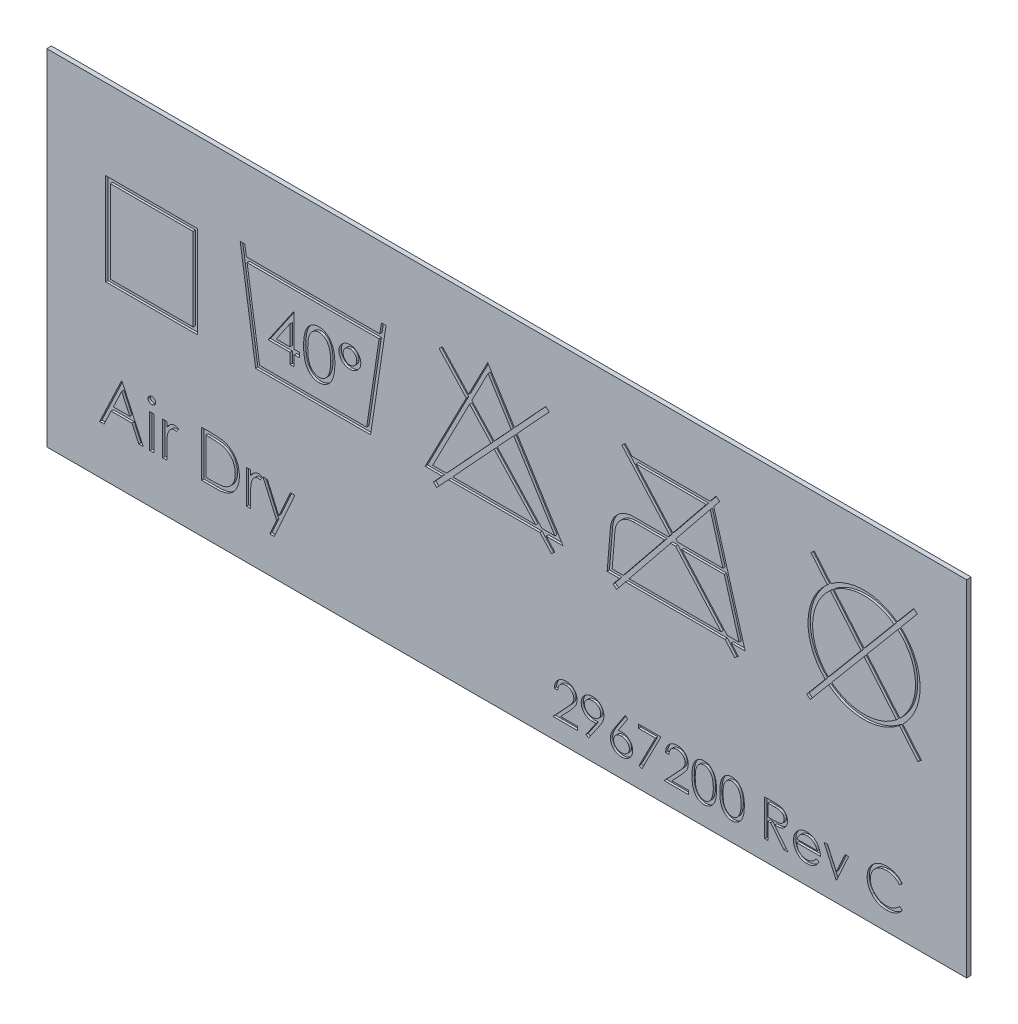
SolidWorks part; units mm, degrees
ref_plane "Plan de face" through (0, 0, 0) normal (0, 0, 1) x (1, 0, 0)
ref_plane "Plan de dessus" through (0, 0, 0) normal (0, 1, 0) x (1, 0, 0)
ref_plane "Plan de droite" through (0, 0, 0) normal (1, 0, 0) x (0, 0, -1)
sketch "Esquisse1" plane through (0, 0, 0) normal (0, 0, 1) x (1, 0, 0)
  line L1 (0, 0) -> (40, 0)
  line L3 (0, 15) -> (40, 15)
  line L4 (40, 0) -> (40, 15)
  line L5 (0, 15) -> (0, 0)
  point P7 (0, 0)
  dimension "D1" = 40
  dimension "D2" = 15
extrude "Extrusion1" add sketch "Esquisse1" along normal blind 0.2
sketch "Esquisse2" plane through (0, 0, 0.2) normal (0, 0, 1) x (1, 0, 0)
  line L0 (0, 7.5) -> (40, 7.5) construction
  line L2 (40, 0) -> (40, 15) construction
  line L3 (2.7616, 11.3) -> (6.3616, 11.3)
  line L4 (2.5616, 7.5) -> (6.5616, 7.5)
  line L5 (2.5616, 7.5) -> (2.5616, 11.5)
  line L6 (2.5616, 11.5) -> (6.5616, 11.5)
  line L7 (6.5616, 7.5) -> (6.5616, 11.5)
  line L8 (6.3616, 7.7) -> (6.3616, 11.3)
  line L9 (2.7616, 7.7) -> (6.3616, 7.7)
  line L10 (2.7616, 7.7) -> (2.7616, 11.3)
  line L11 (0, 15) -> (0, 0) construction
  dimension "D1" = 4
  dimension "D2" = 4
  dimension "D4" = 2.5616
  dimension "D3" = 0.2
extrude "Extrusion2" cut sketch "Esquisse2" against normal blind 0.1
sketch "Esquisse4" plane through (0, 0, 0.2) normal (0, 0, 1) x (1, 0, 0)
  line L0 (9.0813, 7.5) -> (14.0813, 7.5)
  line L1 (9.0813, 7.5) -> (8.4097, 11.9496)
  line L2 (13.9092, 7.7) -> (14.4525, 11.3)
  line L3 (14.0813, 7.5) -> (14.7528, 11.9496)
  line L4 (9.2534, 7.7) -> (13.9092, 7.7)
  line L5 (9.2534, 7.7) -> (8.71, 11.3)
  line L6 (8.4097, 11.9496) -> (8.612, 11.9496)
  line L7 (14.7528, 11.9496) -> (14.5506, 11.9496)
  line L8 (8.6799, 11.5) -> (14.4827, 11.5)
  line L9 (13.9092, 7.7) -> (14.5551, 11.9795) construction
  line L10 (9.2534, 7.7) -> (8.6075, 11.9795) construction
  line L11 (8.71, 11.3) -> (14.4525, 11.3)
  line L12 (8.6799, 11.5) -> (8.612, 11.9496)
  line L13 (8.6799, 11.3) -> (14.4827, 11.3) construction
  line L14 (14.4827, 11.5) -> (14.5506, 11.9496)
  dimension "D1" = 0.2
  dimension "D2" = 0.2
extrude "Extrusion3" cut sketch "Esquisse4" against normal blind 0.1
sketch "Esquisse5" plane through (0, 0, 0.2) normal (0, 0, 1) x (1, 0, 0)
  line L0 (16.4542, 7.5) -> (17.1941, 7.5)
  line L1 (19.4542, 5.2543) -> (19.4542, 13.8877) construction
  line L2 (16.4542, 7.5) -> (18.2422, 10.9621)
  line L3 (19.174, 12.7662) -> (20.3364, 10.9)
  line L4 (20.3053, 10.5716) -> (22.094, 7.7)
  line L5 (19.1902, 12.3618) -> (20.1957, 10.7476)
  line L6 (16.7826, 7.7) -> (17.379, 7.7)
  line L7 (17.2087, 12.375) -> (18.3398, 11.1511)
  line L8 (17.0618, 12.2393) -> (18.2422, 10.9621)
  line L9 (21.8466, 12.2393) -> (20.4461, 10.7239)
  line L10 (21.6997, 12.375) -> (20.3364, 10.9)
  line L11 (19.318, 9.7981) -> (17.379, 7.7)
  line L12 (19.5904, 9.7981) -> (21.5294, 7.7)
  line L13 (19.4542, 9.6507) -> (17.6513, 7.7)
  line L14 (17.2087, 12.375) -> (22.0963, 7.0867) construction
  line L15 (19.4542, 9.6507) -> (21.2571, 7.7)
  line L16 (17.2087, 12.375) -> (17.0618, 12.2393)
  line L17 (17.0618, 12.2393) -> (21.9494, 6.9509) construction
  line L18 (21.6997, 12.375) -> (21.8466, 12.2393)
  line L19 (16.8121, 7.0867) -> (16.959, 6.9509)
  line L20 (21.9494, 6.9509) -> (22.0963, 7.0867)
  line L21 (16.7826, 7.7) -> (18.3866, 10.8058)
  line L22 (18.4842, 10.9949) -> (19.4542, 9.9454)
  line L23 (16.4542, 7.5) -> (19.4542, 12.375) construction
  line L24 (19.1902, 12.3618) -> (22.2844, 7.3943) construction
  line L25 (18.3866, 10.8058) -> (19.318, 9.7981)
  line L26 (16.8121, 7.7) -> (19.4542, 11.9934) construction
  line L27 (16.6319, 7.4082) -> (19.1902, 12.3618) construction
  line L28 (20.4461, 10.7239) -> (22.4542, 7.5)
  line L29 (22.0963, 7.7) -> (19.4542, 11.9934) construction
  line L30 (20.1957, 10.7476) -> (19.4542, 9.9454)
  line L31 (22.4542, 7.5) -> (19.4542, 12.375) construction
  line L32 (20.3053, 10.5716) -> (19.5904, 9.7981)
  line L33 (17.6513, 7.7) -> (21.2571, 7.7)
  line L34 (17.1941, 7.5) -> (16.8121, 7.0867)
  line L35 (16.8121, 7.7) -> (22.0963, 7.7) construction
  line L36 (17.4665, 7.5) -> (21.4419, 7.5)
  line L37 (17.4665, 7.5) -> (16.959, 6.9509)
  line L38 (16.4542, 7.5) -> (22.4542, 7.5) construction
  line L39 (21.7143, 7.5) -> (22.0963, 7.0867)
  line L40 (21.5294, 7.7) -> (22.094, 7.7)
  line L41 (21.4419, 7.5) -> (21.9494, 6.9509)
  line L42 (21.7143, 7.5) -> (22.4542, 7.5)
  line L43 (18.3398, 11.1511) -> (19.174, 12.7662)
  line L44 (19.174, 12.7662) -> (22.4542, 7.5) construction
  line L45 (18.4842, 10.9949) -> (19.1902, 12.3618)
  line L46 (16.4542, 7.5) -> (19.174, 12.7662) construction
  dimension "D1" = 0.2
  dimension "D2" = 0.2
  dimension "D3" = 0.2
extrude "Extrusion4" cut sketch "Esquisse5" against normal blind 0.1
sketch "Esquisse6" plane through (0, 0, 0.2) normal (0, 0, 1) x (1, 0, 0)
  line L0 (24.369, 7.5) -> (24.9075, 7.5)
  line L1 (30.369, 7.5) -> (29.0012, 12.2571)
  line L2 (25.4478, 12.375) -> (28.8394, 12.375)
  line L3 (29.4038, 10.1331) -> (27.4328, 10.1331)
  line L4 (24.369, 7.5) -> (24.509, 9.2145)
  line L5 (27.2226, 10.3705) -> (25.6249, 12.175)
  line L6 (25.3142, 12.375) -> (28.9674, 12.375) construction
  line L7 (25.6249, 12.175) -> (28.6781, 12.175)
  line L8 (30.1034, 7.7) -> (29.4613, 9.9331)
  line L9 (24.586, 7.7) -> (25.0688, 7.7)
  line L10 (24.586, 7.7) -> (24.7084, 9.1982)
  line L11 (29.4613, 9.9331) -> (27.6099, 9.9331)
  line L12 (29.4038, 10.1331) -> (28.8478, 12.0669)
  line L13 (29.6119, 10.1331) -> (25.5057, 10.1331) construction
  line L14 (29.6119, 9.9331) -> (25.5057, 9.9331) construction
  line L15 (24.7804, 7.0239) -> (25.1644, 7.5)
  line L16 (30.1034, 7.7) -> (28.8168, 12.175) construction
  line L17 (25.3142, 12.175) -> (28.8168, 12.175) construction
  line L18 (30.0715, 7.153) -> (29.7642, 7.5)
  line L19 (24.6247, 7.1494) -> (24.9075, 7.5)
  line L20 (29.9217, 7.0204) -> (29.4971, 7.5)
  line L21 (30.369, 7.5) -> (28.9674, 12.375) construction
  line L22 (27.2226, 10.3705) -> (28.6781, 12.175)
  line L23 (27.0312, 10.1331) -> (25.5057, 10.1331)
  line L24 (27.0953, 10.2126) -> (25.0058, 12.5725)
  line L25 (27.3571, 10.2186) -> (28.8478, 12.0669)
  line L26 (26.8699, 9.9331) -> (25.5057, 9.9331)
  line L27 (27.3428, 9.9331) -> (27.1268, 9.9331)
  line L28 (27.4328, 10.1331) -> (27.3571, 10.2186)
  line L29 (27.0312, 10.1331) -> (27.0953, 10.2126)
  line L30 (25.1556, 12.7051) -> (25.0058, 12.5725)
  line L31 (29.1028, 12.7016) -> (29.2584, 12.576)
  line L32 (29.9217, 7.0204) -> (30.0715, 7.153)
  line L33 (24.6247, 7.1494) -> (24.7804, 7.0239)
  line L34 (28.8394, 12.375) -> (29.1028, 12.7016)
  line L35 (29.0012, 12.2571) -> (29.2584, 12.576)
  line L36 (25.4478, 12.375) -> (25.1556, 12.7051)
  line L37 (29.32, 7.7) -> (27.3428, 9.9331)
  line L38 (29.5871, 7.7) -> (30.1034, 7.7)
  line L39 (29.5871, 7.7) -> (27.6099, 9.9331)
  line L40 (24.586, 7.7) -> (30.1034, 7.7) construction
  line L41 (29.7642, 7.5) -> (30.369, 7.5)
  line L42 (25.3257, 7.7) -> (29.32, 7.7)
  line L43 (24.369, 7.5) -> (30.369, 7.5) construction
  line L44 (25.0688, 7.7) -> (26.8699, 9.9331)
  line L45 (25.1644, 7.5) -> (29.4971, 7.5)
  line L46 (25.3257, 7.7) -> (27.1268, 9.9331)
  arc A0 (25.5057, 10.1331) -> (24.509, 9.2145) centre (25.5057, 9.1331) ccw
  arc A1 (25.5057, 9.9331) -> (24.7084, 9.1982) centre (25.5057, 9.1331) ccw
  dimension "D1" = 1
  dimension "D2" = 0.2
extrude "Extrusion5" cut sketch "Esquisse6" against normal blind 0.1
sketch "Esquisse8" plane through (0, 0, 0.2) normal (0, 0, 1) x (1, 0, 0)
  line L0 (35.4099, 10.0333) -> (33.9827, 8.3313)
  line L1 (35.5404, 13.5278) -> (35.5404, 6.6162) construction
  line L3 (35.6709, 10.0333) -> (37.0981, 8.3313)
  line L4 (33.2263, 12.6373) -> (33.9449, 11.7803)
  line L5 (37.7013, 12.7658) -> (36.9794, 11.9049)
  line L6 (33.3795, 12.7658) -> (34.1014, 11.9049)
  line L7 (37.8545, 12.6373) -> (37.1359, 11.7803)
  line L8 (35.5404, 9.8777) -> (34.1324, 8.1986)
  line L9 (35.5404, 9.8777) -> (36.9484, 8.1986)
  line L10 (37.0074, 11.627) -> (35.6709, 10.0333)
  line L11 (36.8506, 11.7513) -> (35.5404, 10.1889)
  line L12 (34.2302, 11.7513) -> (35.5404, 10.1889)
  line L13 (34.0734, 11.627) -> (35.4099, 10.0333)
  line L14 (33.8538, 8.1777) -> (33.0484, 7.2172)
  line L15 (34.0038, 8.0453) -> (33.2017, 7.0887)
  line L16 (37.077, 8.0453) -> (37.8791, 7.0887)
  line L17 (37.227, 8.1777) -> (38.0324, 7.2172)
  line L18 (33.2263, 12.6373) -> (33.3795, 12.7658)
  line L19 (37.7013, 12.7658) -> (37.8545, 12.6373)
  line L20 (33.0484, 7.2172) -> (33.2017, 7.0887)
  line L21 (37.8791, 7.0887) -> (38.0324, 7.2172)
  arc A0 (33.9449, 11.7803) -> (33.8538, 8.1777) centre (35.5404, 9.9375) ccw
  arc A1 (34.0734, 11.627) -> (33.9827, 8.3313) centre (35.5404, 9.9375) ccw
  arc A2 (36.9794, 11.9049) -> (34.1014, 11.9049) centre (35.5404, 9.9375) ccw
  circle A3 centre (35.5404, 9.9375) radius 2.4375 construction
  circle A4 centre (35.5404, 9.9375) radius 2.2375 construction
  arc A5 (36.8506, 11.7513) -> (34.2302, 11.7513) centre (35.5404, 9.9375) ccw
  arc A6 (34.0038, 8.0453) -> (37.077, 8.0453) centre (35.5404, 9.9375) ccw
  arc A7 (34.1324, 8.1986) -> (36.9484, 8.1986) centre (35.5404, 9.9375) ccw
  arc A8 (37.0981, 8.3313) -> (37.0074, 11.627) centre (35.5404, 9.9375) ccw
  arc A9 (37.227, 8.1777) -> (37.1359, 11.7803) centre (35.5404, 9.9375) ccw
  point P10 (37.7779, 9.9375)
  point P19 (37.8714, 10.6502)
  dimension "D1" = 0.2
extrude "Extrusion6" cut sketch "Esquisse8" against normal blind 0.1
sketch "Esquisse9" plane through (0, 0, 0.2) normal (0, 0, 1) x (1, 0, 0)
  line L0 (2.1948, 2.1102) -> (17.6302, 2.1102) construction
  text T0 "Air Dry" font "Century Gothic" height 2
extrude "Extrusion7" cut sketch "Esquisse9" against normal blind 0.1
sketch "Esquisse10" plane through (0, 0, 0.2) normal (0, 0, 1) x (1, 0, 0)
  line L0 (9.5523, 8.3916) -> (13.5929, 8.3916) construction
  text T0 "40°" font "Century Gothic" height 2
extrude "Extrusion8" cut sketch "Esquisse10" against normal blind 0.1
sketch "Sketch1" plane through (0, 0, 0.2) normal (0, 0, 1) x (1, 0, 0)
  line L0 (21.2232, 1.0214) -> (33.1385, 1.0214) construction
  text T0 "IPX1"
extrude "Cut-Extrude1" [suppressed] cut sketch "Sketch1" against normal blind 0.1
sketch "Sketch2" plane through (0, 0, 0.2) normal (0, 0, 1) x (1, 0, 0)
  line L0 (21.9505, 0.8585) -> (38.9292, 0.8585) construction
  text T0 "2967200 Rev C" font "Century Gothic" height in points 6
extrude "2967200 P/N" cut sketch "Sketch2" against normal blind 0.1
sketch "Sketch3" plane through (0, 0, 0.2) normal (0, 0, 1) x (1, 0, 0)
  text T0 "2967200P Rev C" font "Century Gothic" height in points 6
extrude "2967200P P/N" [suppressed] cut sketch "Sketch3" against normal blind 0.1
